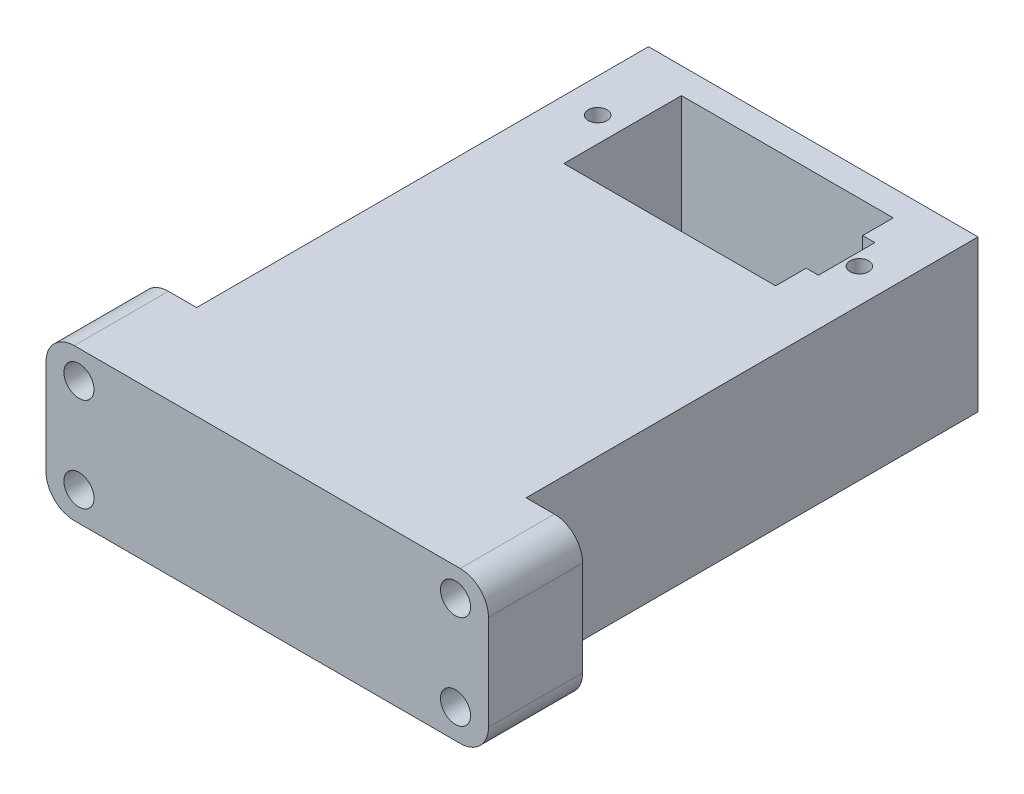
SolidWorks part; units mm, degrees
ref_plane "前视基准面" through (0, 0, 0) normal (0, 0, 1) x (1, 0, 0)
ref_plane "上视基准面" through (0, 0, 0) normal (0, 1, 0) x (1, 0, 0)
ref_plane "右视基准面" through (0, 0, 0) normal (1, 0, 0) x (0, 0, -1)
other "Configuration Table"
sketch "草图2" plane through (0, 0, 0) normal (0, 1, 0) x (1, 0, 0)
  line L1 (-11.25, -6.25) -> (11.25, -6.25)
  line L2 (-11.25, -6.25) -> (-11.25, 6.25)
  line L3 (-11.25, 6.25) -> (11.25, 6.25)
  line L4 (11.25, -6.25) -> (11.25, 6.25)
  line L5 (-11.25, -6.25) -> (11.25, 6.25) construction
  line L6 (-11.25, 6.25) -> (11.25, -6.25) construction
  line L7 (17.5, 9) -> (-17.5, 9)
  line L8 (17.5, 9) -> (17.5, -9)
  line L9 (17.5, -9) -> (-17.5, -9)
  line L10 (-17.5, 9) -> (-17.5, -9)
  line L11 (17.5, 9) -> (-17.5, -9) construction
  line L12 (17.5, -9) -> (-17.5, 9) construction
  point P0 (0, 0)
  point P5 (0, 0)
  dimension "D1" = 22.5
  dimension "D2" = 35
  dimension "D3" = 12.5
extrude "凸台-拉伸1" add sketch "草图2" along normal blind 16.1
sketch "草图3" plane through (0, 16.1, 0) normal (0, 1, 0) x (1, 0, 0)
  line L0 (13.9, 0) -> (-13.9, 0) construction
  circle A0 centre (-13.9, 0) radius 1
  circle A1 centre (13.9, 0) radius 1
  point P4 (0, 0)
  dimension "D1" = 2
  dimension "D2" = 27.8
extrude "切除-拉伸1" cut sketch "草图3" against normal through all
sketch "草图6" plane through (0, 0, 9) normal (0, 0, 1) x (1, 0, 0)
  line L0 (-20, 3.1) -> (-20, 13.1) construction
  line L1 (-17.5, 16.1) -> (-23.5, 16.1)
  line L2 (-17.5, 16.1) -> (-17.5, 0)
  line L3 (-17.5, 0) -> (-23.5, 0)
  line L4 (-23.5, 16.1) -> (-23.5, 0)
  line L5 (17.5, 16.1) -> (23.5, 16.1)
  line L6 (17.5, 16.1) -> (17.5, 0)
  line L7 (17.5, 0) -> (23.5, 0)
  line L8 (23.5, 16.1) -> (23.5, 0)
  line L9 (0, 0) -> (0, 16.1) construction
  line L10 (-17.5, 16.1) -> (17.5, 16.1) construction
  circle A0 centre (-20, 13.1) radius 1.6
  circle A1 centre (-20, 3.1) radius 1.6
  circle A2 centre (20, 3.1) radius 1.6
  circle A3 centre (20, 13.1) radius 1.6
  point P13 (-20, 8.1)
  dimension "D1" = 6
  dimension "D2" = 3.2
  dimension "D3" = 40
  dimension "D4" = 10
  dimension "D5" = 16.1
  dimension "D6" = 3
ref_plane "基准面1" through (0, 8.05, 0) normal (0, 1, 0) x (1, 0, 0)
sketch "草图8" plane through (0, 16.1, 0) normal (0, 1, 0) x (1, 0, 0)
  line L0 (11.25, 0) -> (11.25, -3) construction
  line L1 (11.25, -6.25) -> (11.25, 6.25) construction
  line L2 (11.25, -3) -> (12.55, -3) construction
  line L3 (12.55, -3) -> (12.55, 3) construction
  line L5 (12.55, 3) -> (11.25, 3)
  line L6 (12.55, 3) -> (12.55, -3)
  line L7 (12.55, -3) -> (11.25, -3)
  line L8 (11.25, 3) -> (11.25, -3)
  dimension "D1" = 1.3
  dimension "D2" = 6
extrude "切除-拉伸2" cut sketch "草图8" against normal through all
ref_plane "基准面3" through (0, 0, 49) normal (0, 0, 1) x (1, 0, 0)
sketch "草图9" plane through (0, 0, 49) normal (0, 0, 1) x (1, 0, 0)
  line L0 (17.5, 16.1) -> (23.5, 16.1) construction
  line L1 (23.5, 16.1) -> (23.5, 0) construction
  line L2 (17.5, 0) -> (23.5, 0) construction
  line L3 (17.5, 16.1) -> (17.5, 0) construction
  line L4 (-17.5, 16.1) -> (-17.5, 0) construction
  line L5 (-17.5, 0) -> (-23.5, 0) construction
  line L6 (-17.5, 16.1) -> (-23.5, 16.1) construction
  line L7 (-23.5, 16.1) -> (-23.5, 0) construction
  line L8 (17.5, 16.1) -> (23.5, 16.1)
  line L9 (23.5, 16.1) -> (23.5, 0)
  line L10 (17.5, 0) -> (23.5, 0)
  line L11 (17.5, 16.1) -> (17.5, 0)
  line L12 (-17.5, 16.1) -> (-17.5, 0)
  line L13 (-17.5, 0) -> (-23.5, 0)
  line L14 (-17.5, 16.1) -> (-23.5, 16.1)
  line L15 (-23.5, 16.1) -> (-23.5, 0)
  circle A0 centre (20, 3.1) radius 1.6 construction
  circle A1 centre (20, 13.1) radius 1.6 construction
  circle A2 centre (-20, 3.1) radius 1.6 construction
  circle A3 centre (-20, 13.1) radius 1.6 construction
  circle A4 centre (20, 3.1) radius 1.6
  circle A5 centre (20, 13.1) radius 1.6
  circle A6 centre (-20, 3.1) radius 1.6
  circle A7 centre (-20, 13.1) radius 1.6
extrude "凸台-拉伸4" add sketch "草图9" against normal blind 10 separate body
sketch "草图10" plane through (0, 0, 49) normal (0, 0, 1) x (1, 0, 0)
  line L0 (0, 0) -> (0, 16.1) construction
  line L1 (-17.5, 16.1) -> (17.5, 16.1)
  line L2 (-17.5, 16.1) -> (-17.5, 0)
  line L3 (-17.5, 0) -> (17.5, 0)
  line L4 (17.5, 16.1) -> (17.5, 0)
  line L5 (-17.5, 16.1) -> (17.5, 0) construction
  line L6 (-17.5, 0) -> (17.5, 16.1) construction
  point P0 (0, 8.05)
extrude "凸台-拉伸5" add sketch "草图10" against normal up to surface (40 mm away) up to face at (0, 8.05, 9)
fillet "圆角1" radius 3 4 edges at (23.5, 0, 44) (23.5, 16.1, 44) (-23.5, 0, 44) (-23.5, 16.1, 44)
